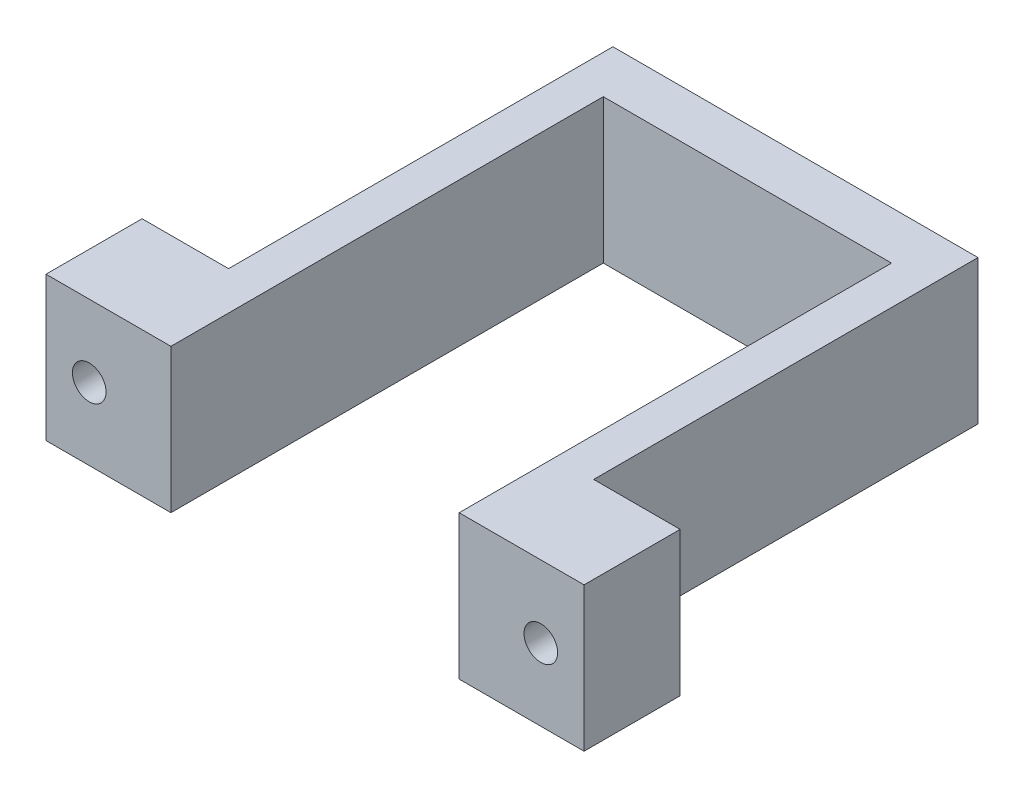
SolidWorks part; units mm, degrees
ref_plane "Front Plane" through (0, 0, 0) normal (0, 0, 1) x (1, 0, 0)
ref_plane "Top Plane" through (0, 0, 0) normal (0, 1, 0) x (1, 0, 0)
ref_plane "Right Plane" through (0, 0, 0) normal (1, 0, 0) x (0, 0, -1)
sketch "Sketch1" plane through (0, 0, 0) normal (0, 1, 0) x (1, 0, 0)
  line L0 (-28, 0) -> (-28, 10)
  line L1 (-28, 10) -> (-19, 10)
  line L2 (-19, 10) -> (-19, 50)
  line L5 (-19, 50) -> (19, 50)
  line L8 (19, 50) -> (19, 10)
  line L9 (19, 10) -> (28, 10)
  line L10 (28, 10) -> (28, 0)
  line L11 (28, 0) -> (15, 0)
  line L12 (15, 0) -> (15, 45)
  line L13 (15, 45) -> (-15, 45)
  line L14 (-15, 45) -> (-15, 0)
  line L15 (-15, 0) -> (-28, 0)
  point P2 (0, 45)
  dimension "D1" = 30
  dimension "D2" = 45
  dimension "D3" = 10
  dimension "D4" = 38
  dimension "D5" = 56
  dimension "D6" = 5
extrude "Boss-Extrude1" add sketch "Sketch1" along normal blind 15
sketch "Sketch8" plane through (0, 0, -10) normal (0, 0, -1) x (-1, 0, 0)
  line L0 (-28, 15) -> (-28, 0) construction
  line L1 (-23.5, 7.5) -> (23.5, 7.5) construction
  line L2 (-28, 15) -> (-19, 15) construction
  circle A0 centre (-23.5, 7.5) radius 1.75
  circle A1 centre (23.5, 7.5) radius 1.75
  point P6 (-28, 7.5)
  point P7 (0, 7.5)
  point P11 (-23.5, 15)
  dimension "D1" = 3.5
extrude "Cut-Extrude5" cut sketch "Sketch8" against normal through all
